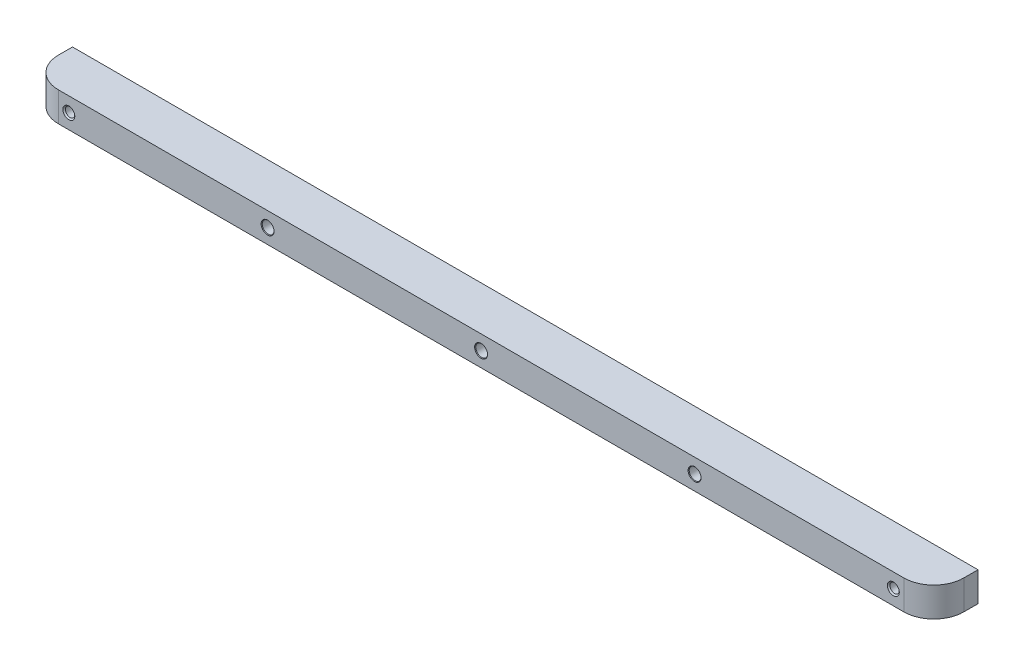
SolidWorks part; units mm, degrees
ref_plane "Front Plane" through (0, 0, 0) normal (0, 0, 1) x (1, 0, 0)
ref_plane "Top Plane" through (0, 0, 0) normal (0, 1, 0) x (1, 0, 0)
ref_plane "Right Plane" through (0, 0, 0) normal (1, 0, 0) x (0, 0, -1)
sketch "Sketch1" plane through (0, 0, 0) normal (0, 1, 0) x (1, 0, 0)
  line L1 (-195.2625, 19.05) -> (195.2625, 19.05)
  line L2 (-195.2625, 19.05) -> (-195.2625, 0)
  line L3 (-195.2625, 0) -> (195.2625, 0)
  line L4 (195.2625, 19.05) -> (195.2625, 0)
  dimension "D1" = 19.05
  dimension "D2" = 390.525
extrude "Extrude1" add sketch "Sketch1" along normal mid plane 12.7
fillet "Fillet1" radius 12.954 2 edges at (195.2625, 0, 0) (-195.2625, 0, 0)
hole_wizard "counterdrilled 10-32" positions "Sketch4" profile "Sketch3" legacy end condition through all
sketch "Sketch4" plane through (0, 0, -19.05) normal (0, 0, -1) x (-1, 0, 0)
  point P0 (-177.8, 0)
  point P1 (177.8, 0)
  dimension "D1" = 177.8
  dimension "D2" = 177.8
sketch "Sketch3" plane through (177.8, 0, -19.05) normal (1, 0, 0) x (0, 1, 0)
  line L0 (0, 0) -> (0, 19.05)
  line L1 (0, 19.05) -> (2.0193, 19.05)
  line L2 (2.0193, 19.05) -> (2.0193, 9.8455)
  line L3 (2.0193, 9.8455) -> (2.5527, 9.525)
  line L4 (2.5527, 9.525) -> (2.5527, 0)
  line L5 (2.5527, 0) -> (0, 0)
  line L6 (0, -6.13) -> (0, 109.2824) construction
  line L7 (-2.0193, 9.8455) -> (-2.5527, 9.525) construction
  line L8 (0, 19.05) -> (-2.0193, 19.05) construction
  dimension "Diameter" = 4.0386
  dimension "Depth" = 19.05
  dimension "C-Drill Diameter" = 5.1054
  dimension "C-Drill Depth" = 9.525
  dimension "C-Drill Angle" = 118
hole_wizard "CBORE for #10 Socket Head Cap Screw1" positions "Sketch6" profile "Sketch5" counterbore size "#10" standard "Ansi Inch" end condition through all
sketch "Sketch6" plane through (0, 0, -19.05) normal (0, 0, -1) x (-1, 0, 0)
  point P0 (-92.075, 0)
  point P1 (0, 0)
  point P3 (92.075, 0)
  dimension "D1" = 92.075
  dimension "D2" = 92.075
sketch "Sketch5" plane through (92.075, 0, -19.05) normal (1, 0, 0) x (0, 1, 0)
  line L0 (0, 0) -> (0, 19.05)
  line L1 (2.5527, 18.8087) -> (2.794, 19.05)
  line L2 (4.3688, 5.334) -> (2.5527, 5.334)
  line L3 (2.5527, 5.334) -> (2.5527, 18.8087)
  line L5 (4.3688, 5.334) -> (4.3688, 0.254)
  line L6 (4.3688, 0.254) -> (4.6228, 0)
  line L7 (4.6228, 0) -> (0, 0)
  line L8 (-4.3688, 0.254) -> (-4.6228, 0) construction
  line L11 (0, -6.35) -> (0, 107.95) construction
  line L12 (2.794, 19.05) -> (0, 19.05)
  line L13 (-2.5527, 18.8087) -> (-2.794, 19.05) construction
  dimension "Thru Hole Dia." = 5.1054
  dimension "Thru Hole Depth" = 19.05
  dimension "C'Bore Dia." = 8.7376
  dimension "C'Bore Depth" = 5.334
  dimension "Near C'Sink Dia." = 9.2456
  dimension "Near C'Sink Angle" = 90
  dimension "Far C'Sink Dia." = 5.588
  dimension "Far C'Sink Angle" = 90
chamfer "Chamfer1" distance 0.254 angle 45 2 edges at (-180.3527, 0, -19.05) (175.2473, 0, -19.05)
chamfer "Chamfer2" distance 0.5588 angle 45 2 edges at (175.7807, 0, 0) (-179.8193, 0, 0)
